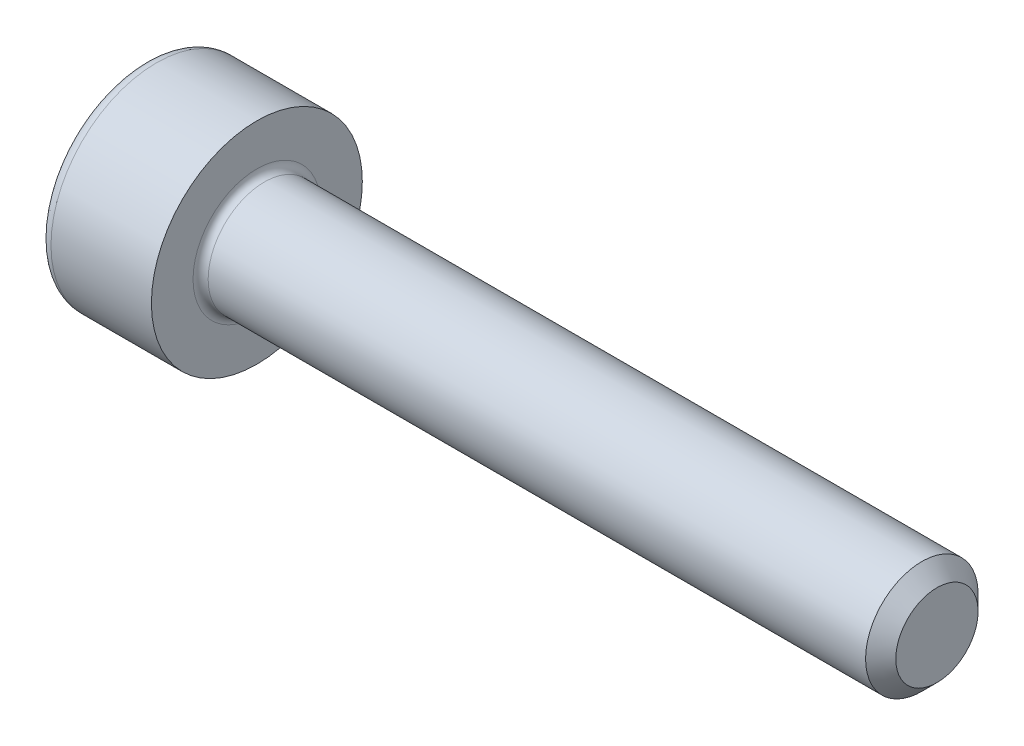
SolidWorks part; units mm, degrees
ref_plane "Спереди" through (0, 0, 0) normal (0, 0, 1) x (1, 0, 0)
ref_plane "Сверху" through (0, 0, 0) normal (0, 1, 0) x (1, 0, 0)
ref_plane "Справа" through (0, 0, 0) normal (1, 0, 0) x (0, 0, -1)
sketch "Sketch1" plane through (0, 0, 0) normal (0, 0, 1) x (1, 0, 0)
  line L0 (0, 0) -> (1.4887, 0)
  line L1 (1.4887, 0) -> (1.4887, 1.3957)
  line L2 (1.4887, 1.3957) -> (0, 1.3957)
  line L3 (0, 1.3957) -> (0, 0)
  line L4 (1.4887, 0) -> (10.4887, 0)
  line L5 (10.4887, 0) -> (10.4887, 0.7444)
  line L6 (10.4887, 0.7444) -> (1.4887, 0.7444)
  dimension "D1" = 9
revolve "Revolve1" add sketch "Sketch1" angle 360 about L0
fillet "Fillet1" radius 0.1 1 edges at (1.4887, 0, 0.7444)
fillet "Fillet2" radius 0.16 1 edges at (0, 0, 1.3957)
chamfer "Chamfer1" distance 0.2 angle 45 1 edges at (10.4887, 0, 0.7444)
sketch "Sketch2" plane through (0, 0, 0) normal (-1, 0, 0) x (0, 0, 1)
  line L1 (0, 0.8776) -> (-0.76, 0.4388)
  line L2 (-0.76, 0.4388) -> (-0.76, -0.4388)
  line L3 (-0.76, -0.4388) -> (0, -0.8776)
  line L4 (0, -0.8776) -> (0.76, -0.4388)
  line L5 (0.76, -0.4388) -> (0.76, 0.4388)
  line L6 (0.76, 0.4388) -> (0, 0.8776)
  circle A0 centre (0, 0) radius 0.76 construction
extrude "Extrude1" cut sketch "Sketch2" against normal blind 0.7
